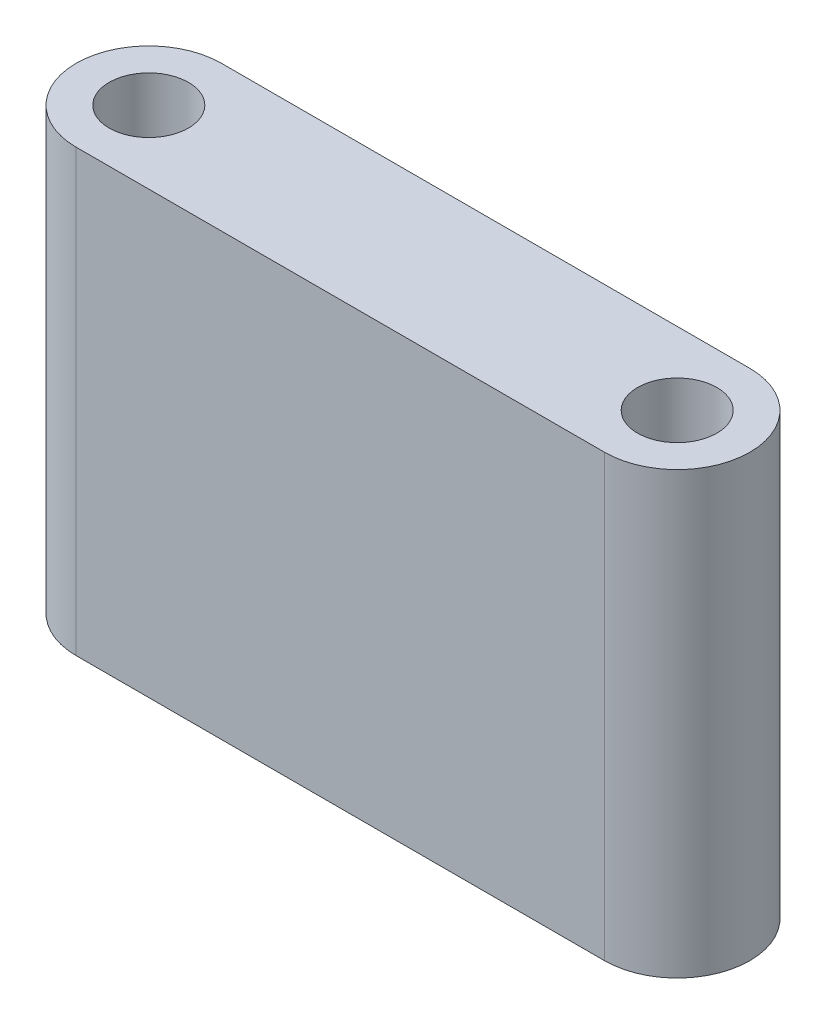
SolidWorks part; units mm, degrees
ref_plane "Front Plane" through (0, 0, 0) normal (0, 0, 1) x (1, 0, 0)
ref_plane "Top Plane" through (0, 0, 0) normal (0, 1, 0) x (1, 0, 0)
ref_plane "Right Plane" through (0, 0, 0) normal (1, 0, 0) x (0, 0, -1)
sketch "Sketch1" plane through (0, 0, 0) normal (0, 1, 0) x (1, 0, 0)
  line L0 (0, 0) -> (24, 0) construction
  line L1 (0, 3.3) -> (24, 3.3)
  line L2 (0, -3.3) -> (24, -3.3)
  line L3 (12, 3.3) -> (12, -3.3) construction
  arc A0 (0, 3.3) -> (0, -3.3) centre (0, 0) ccw
  arc A1 (24, -3.3) -> (24, 3.3) centre (24, 0) ccw
  circle A2 centre (0, 0) radius 1.8
  circle A3 centre (24, 0) radius 1.8
  point P3 (12, 0)
  dimension "D3" = 3.6
  dimension "D1" = 24
  dimension "D2" = 6.6
extrude "Boss-Extrude1" add sketch "Sketch1" along normal blind 20
